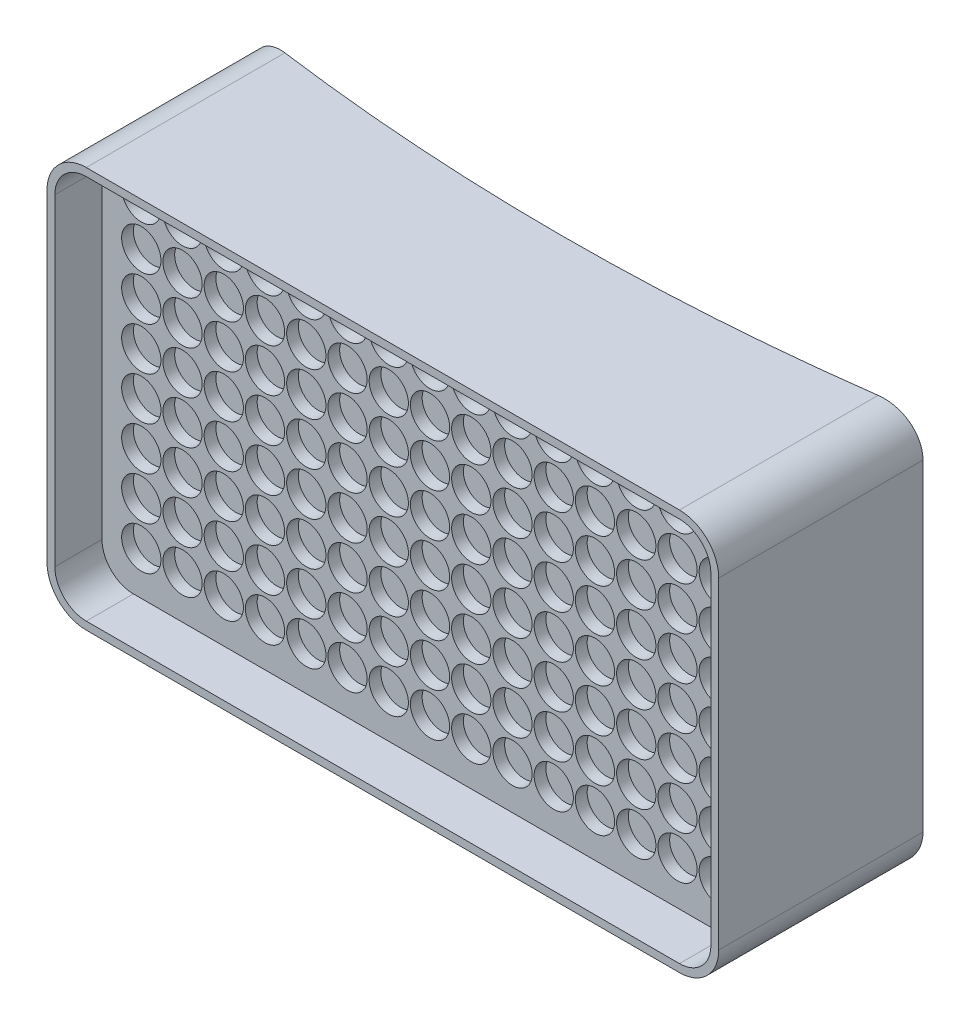
SolidWorks part; units mm, degrees
ref_plane "Front Plane" through (0, 0, 0) normal (0, 0, 1) x (1, 0, 0)
ref_plane "Top Plane" through (0, 0, 0) normal (0, 1, 0) x (1, 0, 0)
ref_plane "Right Plane" through (0, 0, 0) normal (1, 0, 0) x (0, 0, -1)
sketch "Sketch1" plane through (0, 0, 0) normal (0, 0, 1) x (1, 0, 0)
  line L1 (85.5, 51) -> (-85.5, 51)
  line L2 (85.5, 51) -> (85.5, -51)
  line L3 (85.5, -51) -> (-85.5, -51)
  line L4 (-85.5, 51) -> (-85.5, -51)
  line L5 (85.5, 51) -> (-85.5, -51) construction
  line L6 (85.5, -51) -> (-85.5, 51) construction
  point P0 (0, 0)
  dimension "D1" = 171
  dimension "D2" = 102
extrude "Boss-Extrude1" add sketch "Sketch1" along normal blind 40
fillet "Fillet1" radius 10 4 edges at (85.5, -51, 20) (85.5, 51, 20) (-85.5, -51, 20) (-85.5, 51, 20)
sketch "Sketch3" plane through (0, 0, 40) normal (0, 0, 1) x (1, 0, 0)
  line L0 (75.5, 51) -> (-75.5, 51) construction
  line L1 (-85.5, 41) -> (-85.5, -41) construction
  line L2 (-73.5, 39) -> (-63, 39) construction
  circle A0 centre (-73.5, 39) radius 5
  circle A1 centre (-63, 39) radius 5
  circle A2 centre (-52.5, 39) radius 5
  circle A3 centre (-42, 39) radius 5
  circle A4 centre (-31.5, 39) radius 5
  circle A5 centre (-21, 39) radius 5
  circle A6 centre (-10.5, 39) radius 5
  circle A7 centre (0, 39) radius 5
  circle A8 centre (10.5, 39) radius 5
  circle A9 centre (21, 39) radius 5
  circle A10 centre (31.5, 39) radius 5
  circle A11 centre (42, 39) radius 5
  circle A12 centre (52.5, 39) radius 5
  circle A13 centre (63, 39) radius 5
  circle A14 centre (73.5, 39) radius 5
  circle A15 centre (-63, 28) radius 5
  circle A16 centre (-52.5, 28) radius 5
  circle A17 centre (-42, 28) radius 5
  circle A18 centre (-31.5, 28) radius 5
  circle A19 centre (-21, 28) radius 5
  circle A20 centre (-10.5, 28) radius 5
  circle A21 centre (0, 28) radius 5
  circle A22 centre (10.5, 28) radius 5
  circle A23 centre (21, 28) radius 5
  circle A24 centre (31.5, 28) radius 5
  circle A25 centre (42, 28) radius 5
  circle A26 centre (52.5, 28) radius 5
  circle A27 centre (63, 28) radius 5
  circle A28 centre (73.5, 28) radius 5
  circle A29 centre (-63, 17) radius 5
  circle A30 centre (-52.5, 17) radius 5
  circle A31 centre (-42, 17) radius 5
  circle A32 centre (-31.5, 17) radius 5
  circle A33 centre (-21, 17) radius 5
  circle A34 centre (-10.5, 17) radius 5
  circle A35 centre (0, 17) radius 5
  circle A36 centre (10.5, 17) radius 5
  circle A37 centre (21, 17) radius 5
  circle A38 centre (31.5, 17) radius 5
  circle A39 centre (42, 17) radius 5
  circle A40 centre (52.5, 17) radius 5
  circle A41 centre (63, 17) radius 5
  circle A42 centre (73.5, 17) radius 5
  circle A43 centre (-63, 6) radius 5
  circle A44 centre (-52.5, 6) radius 5
  circle A45 centre (-42, 6) radius 5
  circle A46 centre (-31.5, 6) radius 5
  circle A47 centre (-21, 6) radius 5
  circle A48 centre (-10.5, 6) radius 5
  circle A49 centre (0, 6) radius 5
  circle A50 centre (10.5, 6) radius 5
  circle A51 centre (21, 6) radius 5
  circle A52 centre (31.5, 6) radius 5
  circle A53 centre (42, 6) radius 5
  circle A54 centre (52.5, 6) radius 5
  circle A55 centre (63, 6) radius 5
  circle A56 centre (73.5, 6) radius 5
  circle A57 centre (-63, -5) radius 5
  circle A58 centre (-52.5, -5) radius 5
  circle A59 centre (-42, -5) radius 5
  circle A60 centre (-31.5, -5) radius 5
  circle A61 centre (-21, -5) radius 5
  circle A62 centre (-10.5, -5) radius 5
  circle A63 centre (0, -5) radius 5
  circle A64 centre (10.5, -5) radius 5
  circle A65 centre (21, -5) radius 5
  circle A66 centre (31.5, -5) radius 5
  circle A67 centre (42, -5) radius 5
  circle A68 centre (52.5, -5) radius 5
  circle A69 centre (63, -5) radius 5
  circle A70 centre (73.5, -5) radius 5
  circle A71 centre (-63, -16) radius 5
  circle A72 centre (-52.5, -16) radius 5
  circle A73 centre (-42, -16) radius 5
  circle A74 centre (-31.5, -16) radius 5
  circle A75 centre (-21, -16) radius 5
  circle A76 centre (-10.5, -16) radius 5
  circle A77 centre (0, -16) radius 5
  circle A78 centre (10.5, -16) radius 5
  circle A79 centre (21, -16) radius 5
  circle A80 centre (31.5, -16) radius 5
  circle A81 centre (42, -16) radius 5
  circle A82 centre (52.5, -16) radius 5
  circle A83 centre (63, -16) radius 5
  circle A84 centre (73.5, -16) radius 5
  circle A85 centre (-63, -27) radius 5
  circle A86 centre (-52.5, -27) radius 5
  circle A87 centre (-42, -27) radius 5
  circle A88 centre (-31.5, -27) radius 5
  circle A89 centre (-21, -27) radius 5
  circle A90 centre (-10.5, -27) radius 5
  circle A91 centre (0, -27) radius 5
  circle A92 centre (10.5, -27) radius 5
  circle A93 centre (21, -27) radius 5
  circle A94 centre (31.5, -27) radius 5
  circle A95 centre (42, -27) radius 5
  circle A96 centre (52.5, -27) radius 5
  circle A97 centre (63, -27) radius 5
  circle A98 centre (73.5, -27) radius 5
  circle A99 centre (-63, -38) radius 5
  circle A100 centre (-52.5, -38) radius 5
  circle A101 centre (-42, -38) radius 5
  circle A102 centre (-31.5, -38) radius 5
  circle A103 centre (-21, -38) radius 5
  circle A104 centre (-10.5, -38) radius 5
  circle A105 centre (0, -38) radius 5
  circle A106 centre (10.5, -38) radius 5
  circle A107 centre (21, -38) radius 5
  circle A108 centre (31.5, -38) radius 5
  circle A109 centre (42, -38) radius 5
  circle A110 centre (52.5, -38) radius 5
  circle A111 centre (63, -38) radius 5
  circle A112 centre (73.5, -38) radius 5
  circle A113 centre (-73.5, 28) radius 5
  circle A114 centre (-73.5, 17) radius 5
  circle A115 centre (-73.5, 6) radius 5
  circle A116 centre (-73.5, -5) radius 5
  circle A117 centre (-73.5, -16) radius 5
  circle A118 centre (-73.5, -27) radius 5
  circle A119 centre (-73.5, -38) radius 5
  dimension "D1" = 10
  dimension "D2" = 12
  dimension "D3" = 12
  dimension "D6" = 10.5
  dimension "D4" = 15
  dimension "D5" = 8
extrude "Cut-Extrude1" cut sketch "Sketch3" against normal blind 3
sketch "Sketch5" plane through (0, 0, 40) normal (0, 0, 1) x (1, 0, 0)
  line L0 (-75.5, 49) -> (75.5, 49)
  line L1 (-75.5, 51) -> (75.5, 51)
  line L2 (-85.5, 41) -> (-85.5, -41)
  line L3 (-75.5, -51) -> (75.5, -51)
  line L4 (85.5, 41) -> (85.5, -41)
  line L5 (-85.5, 51) -> (85.5, -51) construction
  line L6 (-85.5, -51) -> (85.5, 51) construction
  line L7 (83.5, 41) -> (83.5, -41)
  line L8 (-75.5, -49) -> (75.5, -49)
  line L9 (-83.5, 41) -> (-83.5, -41)
  arc A0 (75.5, -51) -> (85.5, -41) centre (75.5, -41) ccw
  arc A1 (-85.5, -41) -> (-75.5, -51) centre (-75.5, -41) ccw
  arc A2 (-75.5, 51) -> (-85.5, 41) centre (-75.5, 41) ccw
  arc A3 (75.5, 51) -> (85.5, 41) centre (75.5, 41) cw
  arc A4 (75.5, 49) -> (83.5, 41) centre (75.5, 41) cw
  arc A5 (75.5, -49) -> (83.5, -41) centre (75.5, -41) ccw
  arc A6 (-83.5, -41) -> (-75.5, -49) centre (-75.5, -41) ccw
  arc A7 (-75.5, 49) -> (-83.5, 41) centre (-75.5, 41) ccw
  point P0 (0, 0)
  dimension "D3" = 10
  dimension "D1" = 171
  dimension "D2" = 102
  dimension "D4" = 2
extrude "Boss-Extrude4" add sketch "Sketch5" along normal blind 12
sketch "Sketch6" plane through (0, 0, 0) normal (0, 1, 0) x (1, 0, 0)
  circle A0 centre (0, 558.4933) radius 565
  dimension "D1" = 1130
extrude "Cut-Extrude2" cut sketch "Sketch6" against normal through all both and the other way through all
